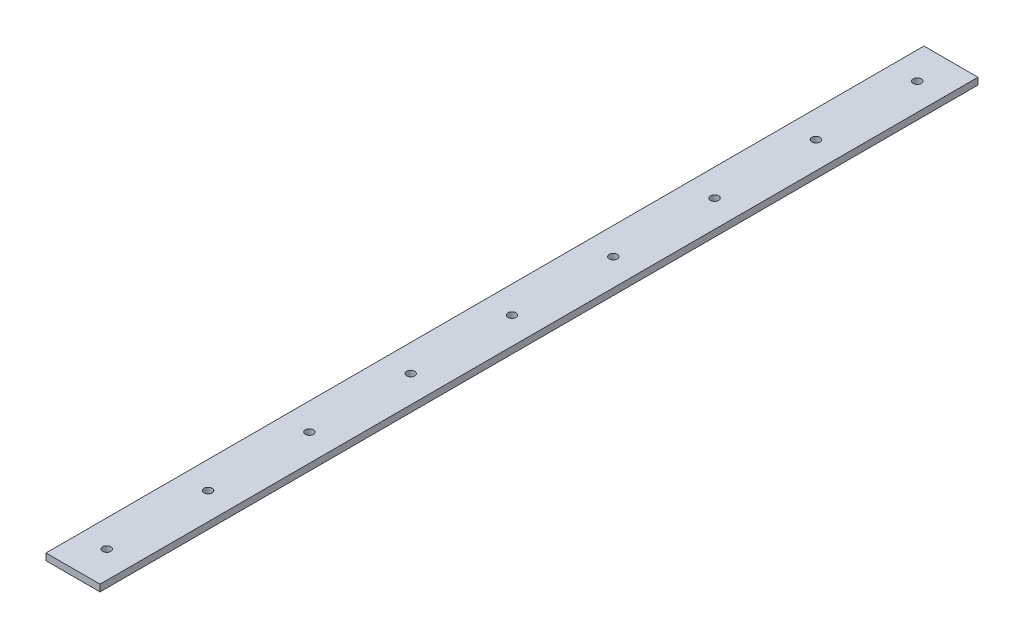
SolidWorks part; units mm, degrees
material "Plain Carbon Steel"
ref_plane "Front Plane" through (0, 0, 0) normal (0, 0, 1) x (1, 0, 0)
ref_plane "Top Plane" through (0, 0, 0) normal (0, 1, 0) x (1, 0, 0)
ref_plane "Right Plane" through (0, 0, 0) normal (1, 0, 0) x (0, 0, -1)
sketch "Sketch1" plane through (0, 0, 0) normal (0, 1, 0) x (1, 0, 0)
  line L1 (-20, -325) -> (20, -325)
  line L2 (-20, -325) -> (-20, 325)
  line L3 (-20, 325) -> (20, 325)
  line L4 (20, -325) -> (20, 325)
  line L5 (-20, -325) -> (20, 325) construction
  line L6 (-20, 325) -> (20, -325) construction
  point P0 (0, 0)
  dimension "D1" = 40
  dimension "D2" = 650
extrude "Boss-Extrude1" add sketch "Sketch1" along normal blind 5
sketch "Sketch2" plane through (0, 0, 0) normal (0, 1, 0) x (1, 0, 0)
  line L0 (-2.75, 0) -> (2.75, 0) construction
  circle A14 centre (0, 0) radius 3
  circle A15 centre (0, 75) radius 3
  circle A16 centre (0, 150) radius 3
  circle A17 centre (0, 225) radius 3
  circle A18 centre (0, 300) radius 3
  circle A19 centre (0, -300) radius 3
  circle A20 centre (0, -225) radius 3
  circle A21 centre (0, -150) radius 3
  circle A22 centre (0, -75) radius 3
  dimension "D1" = 6
extrude "Cut-Extrude1" cut sketch "Sketch2" along normal through all both and the other way through all
